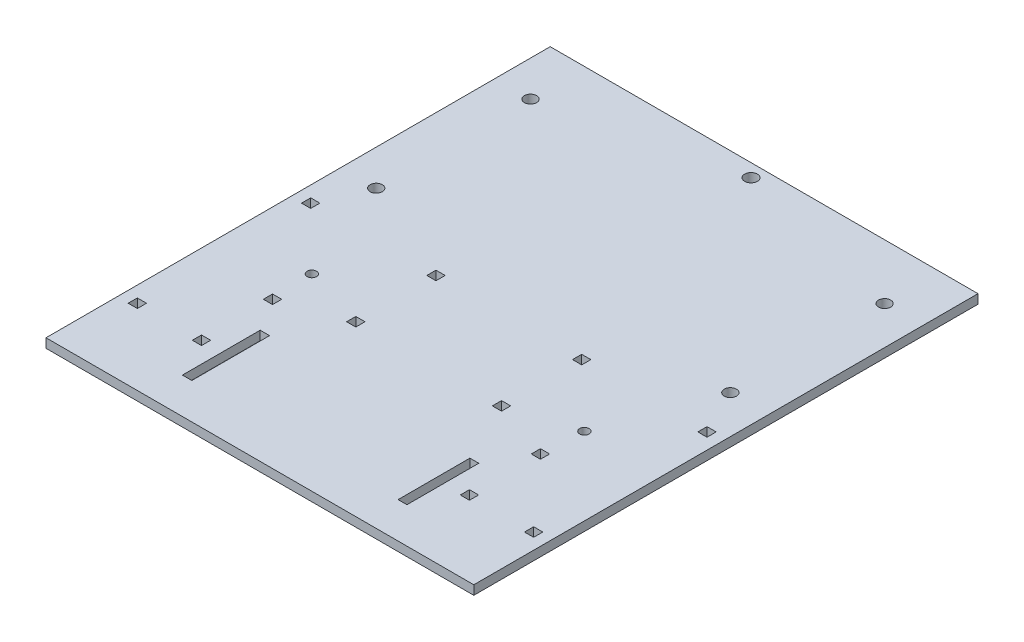
SolidWorks part; units mm, degrees
ref_plane "Front Plane" through (0, 0, 0) normal (0, 0, 1) x (1, 0, 0)
ref_plane "Top Plane" through (0, 0, 0) normal (0, 1, 0) x (1, 0, 0)
ref_plane "Right Plane" through (0, 0, 0) normal (1, 0, 0) x (0, 0, -1)
sketch "Sketch1" plane through (0, 0, 0) normal (0, 1, 0) x (1, 0, 0)
  line L1 (-70, 82.5) -> (70, 82.5)
  line L2 (-70, 82.5) -> (-70, -82.5)
  line L3 (-70, -82.5) -> (70, -82.5)
  line L4 (70, 82.5) -> (70, -82.5)
  line L5 (-70, 82.5) -> (70, -82.5) construction
  line L6 (-70, -82.5) -> (70, 82.5) construction
  line L54 (-22.3437, -2.5319) -> (-22.3437, 0.4681)
  line L55 (-22.3437, 0.4681) -> (-25.3437, 0.4681)
  line L56 (-25.3437, 0.4681) -> (-25.3437, -2.5319)
  line L57 (-25.3437, -2.5319) -> (-22.3437, -2.5319)
  line L58 (-63.3437, -2.5319) -> (-63.3437, 0.4681)
  line L59 (-63.3437, 0.4681) -> (-66.3437, 0.4681)
  line L60 (-66.3437, 0.4681) -> (-66.3437, -2.5319)
  line L61 (-66.3437, -2.5319) -> (-63.3437, -2.5319)
  line L62 (-63.3437, -59.2681) -> (-63.3437, -56.2681)
  line L63 (-63.3437, -56.2681) -> (-66.3437, -56.2681)
  line L64 (-66.3437, -56.2681) -> (-66.3437, -59.2681)
  line L65 (-66.3437, -59.2681) -> (-63.3437, -59.2681)
  line L66 (-42.3437, -59.2682) -> (-42.3437, -56.2682)
  line L67 (-42.3437, -56.2682) -> (-45.3437, -56.2682)
  line L68 (-45.3437, -56.2682) -> (-45.3437, -59.2682)
  line L69 (-45.3437, -59.2682) -> (-42.3437, -59.2682)
  line L70 (-42.3437, -36.0319) -> (-42.3437, -33.0319)
  line L71 (-42.3437, -33.0319) -> (-45.3437, -33.0319)
  line L72 (-45.3437, -33.0319) -> (-45.3437, -36.0319)
  line L73 (-45.3437, -36.0319) -> (-42.3437, -36.0319)
  line L74 (-22.3437, -28.7681) -> (-22.3437, -25.7681)
  line L75 (-22.3437, -25.7681) -> (-25.3437, -25.7681)
  line L76 (-25.3437, -25.7681) -> (-25.3437, -28.7681)
  line L77 (-25.3437, -28.7681) -> (-22.3437, -28.7681)
  line L78 (42.3437, -33.0319) -> (42.3437, -36.0319)
  line L79 (42.3437, -36.0319) -> (45.3437, -36.0319)
  line L80 (45.3437, -36.0319) -> (45.3437, -33.0319)
  line L81 (45.3437, -33.0319) -> (42.3437, -33.0319)
  line L82 (22.3437, -25.7681) -> (22.3437, -28.7681)
  line L83 (22.3437, -28.7681) -> (25.3437, -28.7681)
  line L84 (25.3437, -28.7681) -> (25.3437, -25.7681)
  line L85 (25.3437, -25.7681) -> (22.3437, -25.7681)
  line L86 (42.3437, -56.2682) -> (42.3437, -59.2682)
  line L87 (42.3437, -59.2682) -> (45.3437, -59.2682)
  line L88 (45.3437, -59.2682) -> (45.3437, -56.2682)
  line L89 (45.3437, -56.2682) -> (42.3437, -56.2682)
  line L90 (63.3437, -56.2681) -> (63.3437, -59.2681)
  line L91 (63.3437, -59.2681) -> (66.3437, -59.2681)
  line L92 (66.3437, -59.2681) -> (66.3437, -56.2681)
  line L93 (66.3437, -56.2681) -> (63.3437, -56.2681)
  line L94 (63.3437, 0.4681) -> (63.3437, -2.5319)
  line L95 (63.3437, -2.5319) -> (66.3437, -2.5319)
  line L96 (66.3437, -2.5319) -> (66.3437, 0.4681)
  line L97 (66.3437, 0.4681) -> (63.3437, 0.4681)
  line L98 (22.3437, 0.4681) -> (22.3437, -2.5319)
  line L99 (22.3437, -2.5319) -> (25.3437, -2.5319)
  line L100 (25.3437, -2.5319) -> (25.3437, 0.4681)
  line L101 (25.3437, 0.4681) -> (22.3437, 0.4681)
  line L103 (-37.0972, -45.3089) -> (-34.026, -45.3089)
  line L104 (-37.0972, -45.3089) -> (-37.0972, -70.7563)
  line L105 (-37.0972, -70.7563) -> (-34.026, -70.7563)
  line L106 (-34.026, -45.3089) -> (-34.026, -70.7563)
  line L107 (33.4785, -47.2544) -> (36.3802, -47.2544)
  line L108 (33.4785, -47.2544) -> (33.4785, -70.7563)
  line L109 (33.4785, -70.7563) -> (36.3802, -70.7563)
  line L110 (36.3802, -47.2544) -> (36.3802, -70.7563)
  circle A7 centre (0, 78.2207) radius 2.0755
  circle A8 centre (-44.5937, -20.9) radius 1.55
  circle A9 centre (44.5937, -20.9) radius 1.55
  circle A10 centre (-58.3565, 13.9252) radius 2
  circle A11 centre (-58.3565, 64.4077) radius 2
  circle A12 centre (57.531, 64.4077) radius 2
  circle A13 centre (57.531, 13.9252) radius 2
  point P0 (0, 0)
  dimension "D1" = 140
  dimension "D2" = 165
extrude "Boss-Extrude1" add sketch "Sketch1" along normal blind 3
